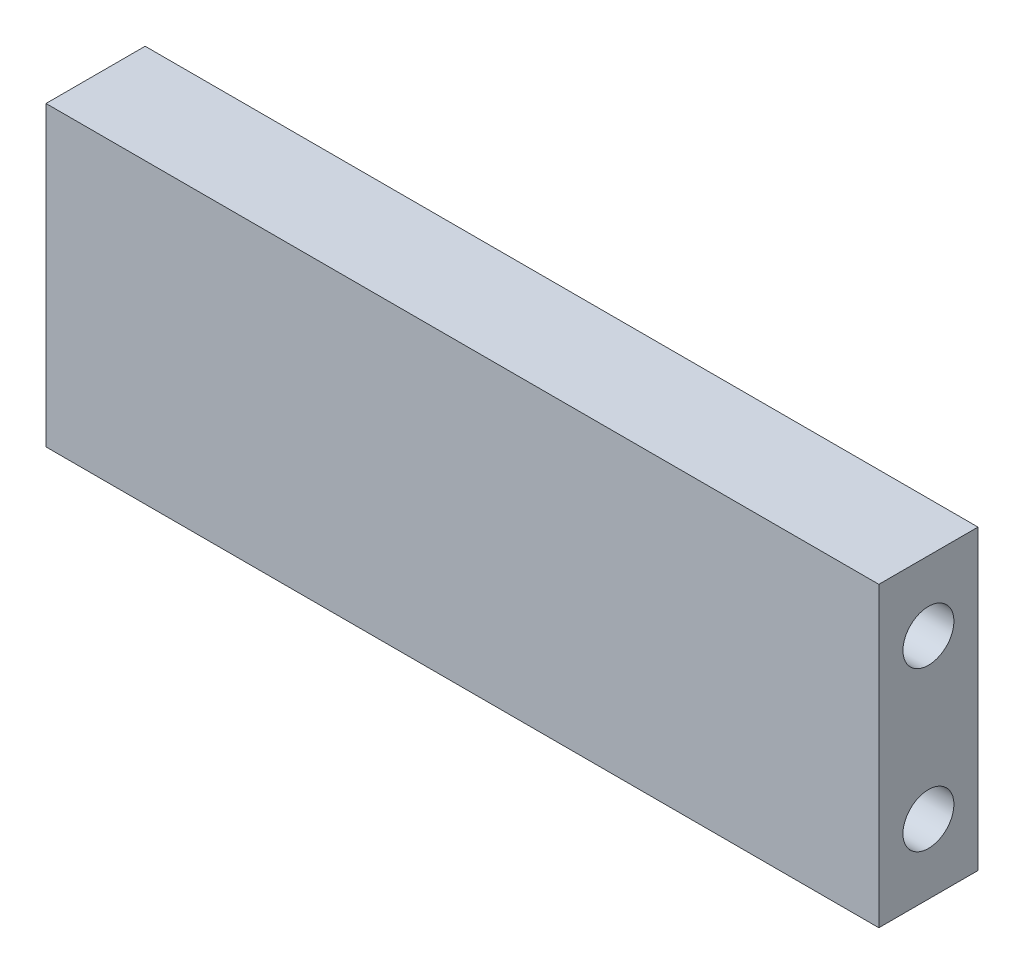
SolidWorks part; units mm, degrees
material "AISI 1020"
ref_plane "Front Plane" through (0, 0, 0) normal (0, 0, 1) x (1, 0, 0)
ref_plane "Top Plane" through (0, 0, 0) normal (0, 1, 0) x (1, 0, 0)
ref_plane "Right Plane" through (0, 0, 0) normal (1, 0, 0) x (0, 0, -1)
sketch "Sketch1" plane through (0, 0, 0) normal (0, 0, 1) x (1, 0, 0)
  line L1 (-53.34, -19.05) -> (53.34, -19.05)
  line L2 (-53.34, -19.05) -> (-53.34, 19.05)
  line L3 (-53.34, 19.05) -> (53.34, 19.05)
  line L4 (53.34, -19.05) -> (53.34, 19.05)
  line L5 (-53.34, -19.05) -> (53.34, 19.05) construction
  line L6 (-53.34, 19.05) -> (53.34, -19.05) construction
  point P0 (0, 0)
  dimension "D1" = 38.1
  dimension "D2" = 106.68
extrude "Boss-Extrude1" add sketch "Sketch1" along normal blind 12.7
sketch "Sketch2" plane through (53.34, 0, 0) normal (1, 0, 0) x (0, 0, -1)
  line L0 (-12.7, 0) -> (0, 0) construction
  line L1 (-12.7, -19.05) -> (-12.7, 19.05) construction
  circle A0 centre (-6.35, 10.16) radius 3.2639
  circle A1 centre (-6.35, -10.16) radius 3.2639
  dimension "D1" = 6.5278
  dimension "D2" = 10.16
extrude "Cut-Extrude1" cut sketch "Sketch2" against normal blind 22.225
sketch "Sketch3" plane through (-53.34, 0, 0) normal (-1, 0, 0) x (0, 0, 1)
  line L0 (0, 0) -> (12.7, 0) construction
  line L1 (12.7, 19.05) -> (12.7, -19.05) construction
  circle A0 centre (6.35, 10.16) radius 3.2639
  circle A1 centre (6.35, -10.16) radius 3.2639
  dimension "D1" = 10.16
  dimension "D2" = 6.5278
extrude "Cut-Extrude2" cut sketch "Sketch3" against normal blind 22.225
